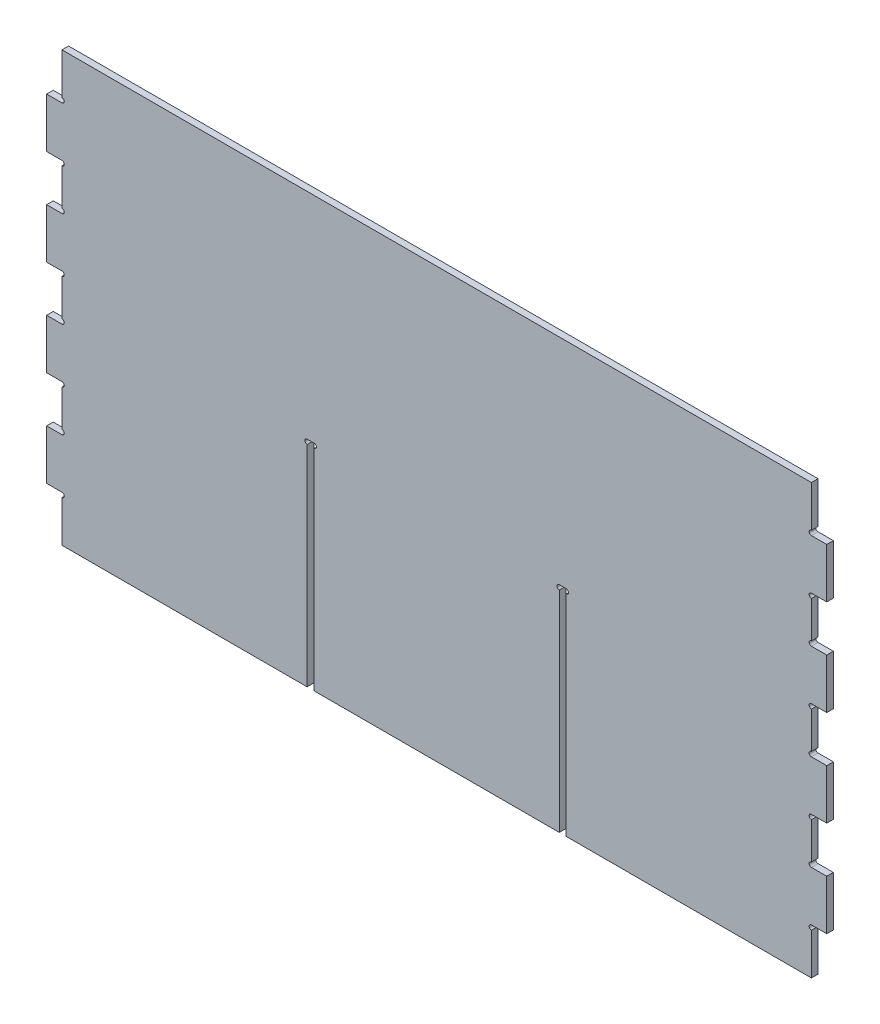
SolidWorks part; units mm, degrees
ref_plane "Front Plane" through (0, 0, 0) normal (0, 0, 1) x (1, 0, 0)
ref_plane "Top Plane" through (0, 0, 0) normal (0, 1, 0) x (1, 0, 0)
ref_plane "Right Plane" through (0, 0, 0) normal (1, 0, 0) x (0, 0, -1)
sketch "Sketch1" plane through (0, 0, 0) normal (0, 0, 1) x (1, 0, 0)
  line L1 (0, 0) -> (646.4808, 0)
  line L2 (0, 0) -> (0, 355.6)
  line L3 (0, 355.6) -> (646.4808, 355.6)
  line L4 (646.4808, 0) -> (646.4808, 355.6)
  dimension "D1" = 646.4808
  dimension "D2" = 355.6
extrude "Boss-Extrude1" add sketch "Sketch1" along normal blind 5.4864
sketch "Sketch4" plane through (0, 0, 5.4864) normal (0, 0, 1) x (1, 0, 0)
  line L0 (0, 0) -> (646.4808, 0) construction
  line L1 (424.8404, 177.8) -> (430.5808, 177.8)
  line L2 (424.8404, 173.99) -> (424.8404, 0)
  line L3 (424.8404, 0) -> (430.5808, 0)
  line L4 (430.5808, 173.99) -> (430.5808, 0)
  line L5 (646.4808, 0) -> (646.4808, 355.6) construction
  line L7 (215.9, 177.8) -> (221.6404, 177.8)
  line L8 (215.9, 173.99) -> (215.9, 0)
  line L9 (215.9, 0) -> (221.6404, 0)
  line L10 (221.6404, 173.99) -> (221.6404, 0)
  arc A0 (430.5808, 173.99) -> (430.5808, 177.8) centre (430.5808, 175.895) ccw
  arc A1 (424.8404, 177.8) -> (424.8404, 173.99) centre (424.8404, 175.895) ccw
  arc A2 (221.6404, 173.99) -> (221.6404, 177.8) centre (221.6404, 175.895) ccw
  arc A3 (215.9, 177.8) -> (215.9, 173.99) centre (215.9, 175.895) ccw
  dimension "D7" = 3.81
  dimension "D8" = 3.81
  dimension "D9" = 3.81
  dimension "D10" = 3.81
  dimension "D1" = 5.7404
  dimension "D2" = 215.9
  dimension "D3" = 177.8
  dimension "D4" = 177.8
  dimension "D5" = 5.7404
  dimension "D6" = 203.2
extrude "Cut-Extrude1" cut sketch "Sketch4" against normal through all
sketch "Sketch5" plane through (0, 0, 5.4864) normal (0, 0, 1) x (1, 0, 0)
  line L0 (323.2404, 0) -> (323.2404, 355.6) construction
  line L1 (0, 0) -> (12.7, 0)
  line L2 (0, 3.81) -> (0, 34.29)
  line L3 (0, 38.1) -> (12.7, 38.1)
  line L4 (12.7, 3.81) -> (12.7, 34.29)
  line L5 (221.6404, 0) -> (424.8404, 0) construction
  line L6 (646.4808, 355.6) -> (0, 355.6) construction
  line L7 (0, 117.475) -> (12.7, 117.475)
  line L8 (12.7, 83.185) -> (12.7, 113.665)
  line L9 (0, 79.375) -> (12.7, 79.375)
  line L10 (0, 83.185) -> (0, 113.665)
  line L11 (0, 196.85) -> (12.7, 196.85)
  line L12 (12.7, 162.56) -> (12.7, 193.04)
  line L13 (0, 158.75) -> (12.7, 158.75)
  line L14 (0, 162.56) -> (0, 193.04)
  line L15 (0, 276.225) -> (12.7, 276.225)
  line L16 (12.7, 241.935) -> (12.7, 272.415)
  line L17 (0, 238.125) -> (12.7, 238.125)
  line L18 (0, 241.935) -> (0, 272.415)
  line L19 (0, 355.6) -> (12.7, 355.6)
  line L20 (12.7, 321.31) -> (12.7, 351.79)
  line L21 (0, 317.5) -> (12.7, 317.5)
  line L22 (0, 321.31) -> (0, 351.79)
  line L23 (646.4808, 321.31) -> (646.4808, 351.79)
  line L24 (646.4808, 317.5) -> (633.7808, 317.5)
  line L25 (633.7808, 321.31) -> (633.7808, 351.79)
  line L26 (646.4808, 355.6) -> (633.7808, 355.6)
  line L27 (646.4808, 241.935) -> (646.4808, 272.415)
  line L28 (646.4808, 238.125) -> (633.7808, 238.125)
  line L29 (633.7808, 241.935) -> (633.7808, 272.415)
  line L30 (646.4808, 276.225) -> (633.7808, 276.225)
  line L31 (646.4808, 162.56) -> (646.4808, 193.04)
  line L32 (646.4808, 158.75) -> (633.7808, 158.75)
  line L33 (633.7808, 162.56) -> (633.7808, 193.04)
  line L34 (646.4808, 196.85) -> (633.7808, 196.85)
  line L35 (646.4808, 83.185) -> (646.4808, 113.665)
  line L36 (646.4808, 79.375) -> (633.7808, 79.375)
  line L37 (633.7808, 83.185) -> (633.7808, 113.665)
  line L38 (646.4808, 117.475) -> (633.7808, 117.475)
  line L39 (633.7808, 3.81) -> (633.7808, 34.29)
  line L40 (646.4808, 38.1) -> (633.7808, 38.1)
  line L41 (646.4808, 3.81) -> (646.4808, 34.29)
  line L42 (646.4808, 0) -> (633.7808, 0)
  line L43 (12.7, 0) -> (12.7, 3.81)
  line L44 (12.7, 351.79) -> (12.7, 355.6)
  line L45 (633.7808, 351.79) -> (633.7808, 355.6)
  line L46 (633.7808, 3.81) -> (633.7808, 0)
  arc A0 (12.7, 34.29) -> (12.7, 38.1) centre (12.7, 36.195) ccw
  arc A1 (0, 38.1) -> (0, 34.29) centre (0, 36.195) ccw
  arc A3 (0, 3.81) -> (0, 0) centre (0, 1.905) ccw
  arc A4 (12.7, 113.665) -> (12.7, 117.475) centre (12.7, 115.57) ccw
  arc A5 (12.7, 79.375) -> (12.7, 83.185) centre (12.7, 81.28) ccw
  arc A6 (0, 83.185) -> (0, 79.375) centre (0, 81.28) ccw
  arc A7 (0, 117.475) -> (0, 113.665) centre (0, 115.57) ccw
  arc A8 (12.7, 193.04) -> (12.7, 196.85) centre (12.7, 194.945) ccw
  arc A9 (12.7, 158.75) -> (12.7, 162.56) centre (12.7, 160.655) ccw
  arc A10 (0, 162.56) -> (0, 158.75) centre (0, 160.655) ccw
  arc A11 (0, 196.85) -> (0, 193.04) centre (0, 194.945) ccw
  arc A12 (12.7, 272.415) -> (12.7, 276.225) centre (12.7, 274.32) ccw
  arc A13 (12.7, 238.125) -> (12.7, 241.935) centre (12.7, 240.03) ccw
  arc A14 (0, 241.935) -> (0, 238.125) centre (0, 240.03) ccw
  arc A15 (0, 276.225) -> (0, 272.415) centre (0, 274.32) ccw
  arc A17 (12.7, 317.5) -> (12.7, 321.31) centre (12.7, 319.405) ccw
  arc A18 (0, 321.31) -> (0, 317.5) centre (0, 319.405) ccw
  arc A19 (0, 355.6) -> (0, 351.79) centre (0, 353.695) ccw
  arc A20 (646.4808, 355.6) -> (646.4808, 351.79) centre (646.4808, 353.695) cw
  arc A21 (646.4808, 321.31) -> (646.4808, 317.5) centre (646.4808, 319.405) cw
  arc A22 (633.7808, 317.5) -> (633.7808, 321.31) centre (633.7808, 319.405) cw
  arc A24 (646.4808, 276.225) -> (646.4808, 272.415) centre (646.4808, 274.32) cw
  arc A25 (646.4808, 241.935) -> (646.4808, 238.125) centre (646.4808, 240.03) cw
  arc A26 (633.7808, 238.125) -> (633.7808, 241.935) centre (633.7808, 240.03) cw
  arc A27 (633.7808, 272.415) -> (633.7808, 276.225) centre (633.7808, 274.32) cw
  arc A28 (646.4808, 196.85) -> (646.4808, 193.04) centre (646.4808, 194.945) cw
  arc A29 (646.4808, 162.56) -> (646.4808, 158.75) centre (646.4808, 160.655) cw
  arc A30 (633.7808, 158.75) -> (633.7808, 162.56) centre (633.7808, 160.655) cw
  arc A31 (633.7808, 193.04) -> (633.7808, 196.85) centre (633.7808, 194.945) cw
  arc A32 (646.4808, 117.475) -> (646.4808, 113.665) centre (646.4808, 115.57) cw
  arc A33 (646.4808, 83.185) -> (646.4808, 79.375) centre (646.4808, 81.28) cw
  arc A34 (633.7808, 79.375) -> (633.7808, 83.185) centre (633.7808, 81.28) cw
  arc A35 (633.7808, 113.665) -> (633.7808, 117.475) centre (633.7808, 115.57) cw
  arc A36 (646.4808, 3.81) -> (646.4808, 0) centre (646.4808, 1.905) cw
  arc A38 (646.4808, 38.1) -> (646.4808, 34.29) centre (646.4808, 36.195) cw
  arc A39 (633.7808, 34.29) -> (633.7808, 38.1) centre (633.7808, 36.195) cw
  arc A40 (12.7, 351.79) -> (12.7, 355.6) centre (12.7, 353.695) ccw [skipped]
  dimension "D3" = 3.81
  dimension "D4" = 3.81
  dimension "D6" = 3.81
  dimension "D1" = 12.7
  dimension "D2" = 38.1
  dimension "D7" = 5
extrude "Cut-Extrude2" cut sketch "Sketch5" against normal through all
fillet "Fillet1" [suppressed] radius 2.54
sketch "Sketch7" plane through (0, 0, 5.4864) normal (0, 0, 1) x (1, 0, 0)
  line L0 (7.62, 393.7237) -> (7.62, 0) construction
  line L1 (12.7, 158.75) -> (12.7, 196.85) construction
  dimension "D1" = 5.08
equation "\"depth\"=14"
equation "\"D2@Sketch1\"=\"depth\""
equation "\"board-thick\"=0.216"
equation "\"D1@Boss-Extrude1\"=\"board-thick\""
equation "\"box-wide\"=8"
equation "\"D2@Sketch4\"=\"box-wide\"+0.5"
equation "\"de\"=7"
equation "\"board-thick-slot\"=0.226"
equation "\"D1@Sketch4\"=\"board-thick-slot\""
equation "\"dog_bone\"=0.15"
equation "\"D7@Sketch4\"=\"dog_bone\""
